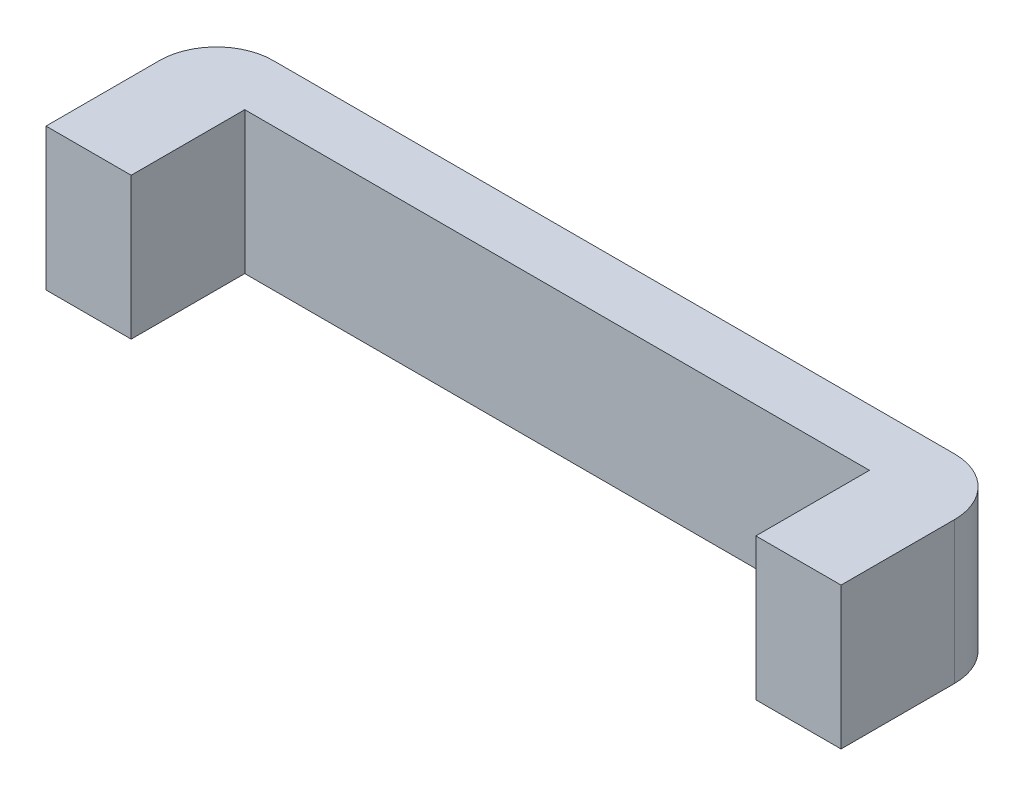
SolidWorks part; units mm, degrees
ref_plane "Front Plane" through (0, 0, 0) normal (0, 0, 1) x (1, 0, 0)
ref_plane "Top Plane" through (0, 0, 0) normal (0, 1, 0) x (1, 0, 0)
ref_plane "Right Plane" through (0, 0, 0) normal (1, 0, 0) x (0, 0, -1)
sketch "Sketch1" plane through (0, 0, 0) normal (0, 1, 0) x (1, 0, 0)
  line L1 (0, 0) -> (35.56, 0)
  line L2 (0, 0) -> (0, -7.62)
  line L3 (0, -7.62) -> (35.56, -7.62)
  line L4 (35.56, 0) -> (35.56, -7.62)
  dimension "D1" = 35.56
  dimension "D2" = 7.62
extrude "Boss-Extrude1" add sketch "Sketch1" along normal blind 6.35
sketch "Sketch2" plane through (0, 6.35, 0) normal (0, 1, 0) x (1, 0, 0)
  line L0 (0, -7.62) -> (35.56, -7.62) construction
  line L1 (3.81, -7.62) -> (31.75, -7.62)
  line L2 (3.81, -7.62) -> (3.81, -2.54)
  line L3 (3.81, -2.54) -> (31.75, -2.54)
  line L4 (31.75, -7.62) -> (31.75, -2.54)
  line L5 (35.56, 0) -> (0, 0) construction
  line L6 (0, 0) -> (0, -7.62) construction
  line L7 (35.56, -7.62) -> (35.56, 0) construction
  dimension "D1" = 2.54
  dimension "D2" = 3.81
  dimension "D3" = 3.81
extrude "Cut-Extrude1" cut sketch "Sketch2" against normal through all
fillet "Fillet1" radius 2.54 2 edges at (0, 3.175, 0) (35.56, 3.175, 0)
